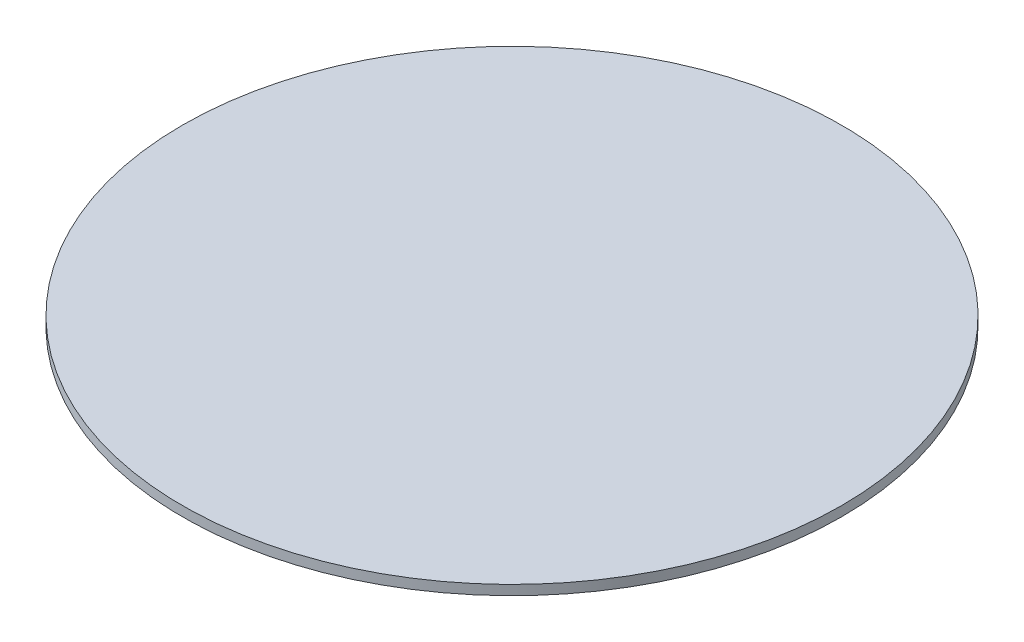
SolidWorks part; units mm, degrees
material "Hexcel AS4C (3000 Filaments)"
ref_plane "Front Plane" through (0, 0, 0) normal (0, 0, 1) x (1, 0, 0)
ref_plane "Top Plane" through (0, 0, 0) normal (0, 1, 0) x (1, 0, 0)
ref_plane "Right Plane" through (0, 0, 0) normal (1, 0, 0) x (0, 0, -1)
sketch "Sketch1" plane through (0, 0, 0) normal (0, 0, 1) x (1, 0, 0)
  line L0 (0, 20.5) -> (0, 18.5) construction
  line L1 (0, 20.5) -> (-67.5, 20.5) construction
  line L2 (0, 18.5) -> (-67.5, 18.5) construction
  line L3 (-67.5, 20.5) -> (-67.5, 18.5) construction
  line L4 (0, 20.5) -> (0, 18.5)
  line L5 (0, 20.5) -> (-67.5, 20.5)
  line L6 (0, 18.5) -> (-67.5, 18.5)
  line L7 (-67.5, 20.5) -> (-67.5, 18.5)
revolve "Revolve1" add sketch "Sketch1" angle 360 about L4
